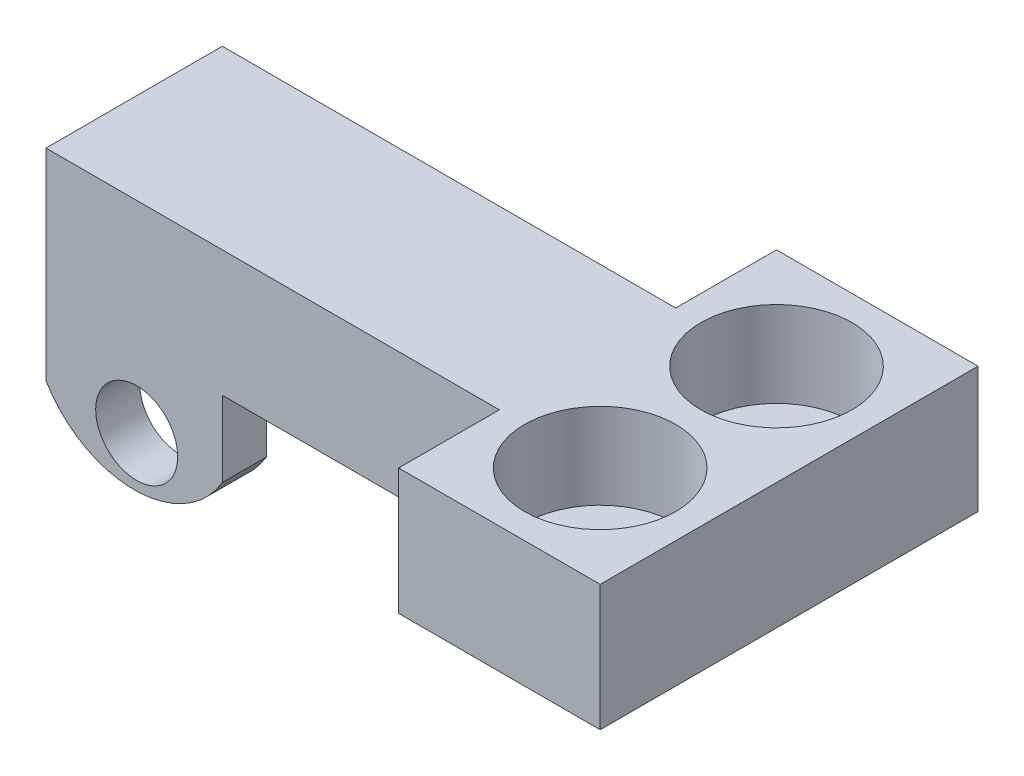
SolidWorks part; units mm, degrees
ref_plane "前视基准面" through (0, 0, 0) normal (0, 0, 1) x (1, 0, 0)
ref_plane "上视基准面" through (0, 0, 0) normal (0, 1, 0) x (1, 0, 0)
ref_plane "右视基准面" through (0, 0, 0) normal (1, 0, 0) x (0, 0, -1)
sketch "草图1" plane through (0, 0, 0) normal (0, 0, 1) x (1, 0, 0)
  line L0 (-19, -3) -> (-26, -3) construction
  line L1 (0, 0) -> (-19, 0)
  line L2 (0, 0) -> (0, 5)
  line L3 (0, 5) -> (-26, 5)
  line L4 (-26, 0) -> (-26, 5)
  line L6 (-26, 0) -> (-26, -3)
  line L8 (-19, 0) -> (-19, -3)
  line L9 (-19, -5) -> (-26, -5) construction
  circle A0 centre (-22.4, -3) radius 1.6285
  arc A1 (-19, -3) -> (-26, -3) centre (-22.5, -0.9375) cw
  dimension "D1" = 26
  dimension "D2" = 5
  dimension "D3" = 5
  dimension "D4" = 2
  dimension "D5" = 22.4
  dimension "D6" = 7
extrude "凸台-拉伸1" add sketch "草图1" along normal blind 15
sketch "草图2" plane through (0, 0, 0) normal (0, -1, 0) x (1, 0, 0)
  line L0 (0, 7.5) -> (-26.0513, 7.5) construction
  line L1 (0, 15) -> (0, 0) construction
  line L2 (-26, 15) -> (-26, 0) construction
  line L3 (-19, 5.75) -> (-26, 5.75)
  line L4 (-19, 5.75) -> (-19, 9.25)
  line L5 (-19, 9.25) -> (-26, 9.25)
  line L6 (-26, 5.75) -> (-26, 9.25)
  line L7 (-19, 5.75) -> (-26, 9.25) construction
  line L8 (-19, 9.25) -> (-26, 5.75) construction
  point P4 (-22.5, 7.5)
  dimension "D1" = 7
  dimension "D2" = 3.5
extrude "切除-拉伸1" cut sketch "草图2" along normal blind 5
sketch "草图5" plane through (0, 0, 0) normal (0, -1, 0) x (1, 0, 0)
  line L0 (0, 7.5) -> (-26, 7.5) construction
  line L1 (0, 15) -> (0, 0) construction
  line L2 (-26, 9.25) -> (-26, 5.75) construction
  line L3 (-8, 15) -> (-8, 0) construction
  line L4 (-19, 15) -> (0, 15) construction
  line L5 (-19, 0) -> (0, 0) construction
  line L7 (-26, 15) -> (-8, 15)
  line L8 (-26, 15) -> (-26, 11)
  line L9 (-26, 11) -> (-8, 11)
  line L10 (-8, 15) -> (-8, 11)
  line L11 (-26, 0) -> (-8, 0)
  line L12 (-26, 0) -> (-26, 4)
  line L13 (-26, 4) -> (-8, 4)
  line L14 (-8, 0) -> (-8, 4)
  dimension "D1" = 8
  dimension "D2" = 4
  dimension "D3" = 4
extrude "切除-拉伸4" cut sketch "草图5" against normal through all both and the other way through all
sketch "草图3" plane through (0, 5, 0) normal (0, 1, 0) x (1, 0, 0)
  line L0 (0, -7.5) -> (-26, -7.5) construction
  line L1 (0, -15) -> (0, 0) construction
  line L2 (-26, -11) -> (-26, -4) construction
  line L3 (-4, 0) -> (-4, -15) construction
  line L4 (0, 0) -> (-8, 0) construction
  line L5 (0, -15) -> (-8, -15) construction
  circle A0 centre (-4, -4) radius 3
  circle A1 centre (-4, -11) radius 3
  dimension "D2" = 6
  dimension "D3" = 6
  dimension "D1" = 4
  dimension "D4" = 4
  dimension "D5" = 4
hole_wizard "打孔尺寸(%根据)内六角圆柱头螺钉的类型1" positions "3D草图4" profile "草图6" counterbore size "M3" standard "GB"
sketch3d "3D草图4"
  point P0 (-4, 5, 4)
  point P3 (-4, 5, 11)
sketch "草图6" plane through (-4, 5, 4) normal (1, 0, 0) x (0, 0, 1)
  line L0 (0, 0) -> (0, 19.5215)
  line L1 (0, 19.5215) -> (1.7, 18.5)
  line L2 (1.7, 18.5) -> (1.7, 3.4)
  line L3 (1.7, 3.4) -> (3, 3.4)
  line L4 (3, 3.4) -> (3, 0)
  line L5 (3, 0) -> (0, 0)
  line L10 (0, 19.5215) -> (-1.7, 18.5) construction
  line L11 (0, -6.35) -> (0, 107.95) construction
  dimension "孔直径" = 3.4
  dimension "孔深度" = 18.5
  dimension "柱形沉头孔直径" = 6
  dimension "柱形沉头孔深度" = 3.4
  dimension "导头角度" = 118
